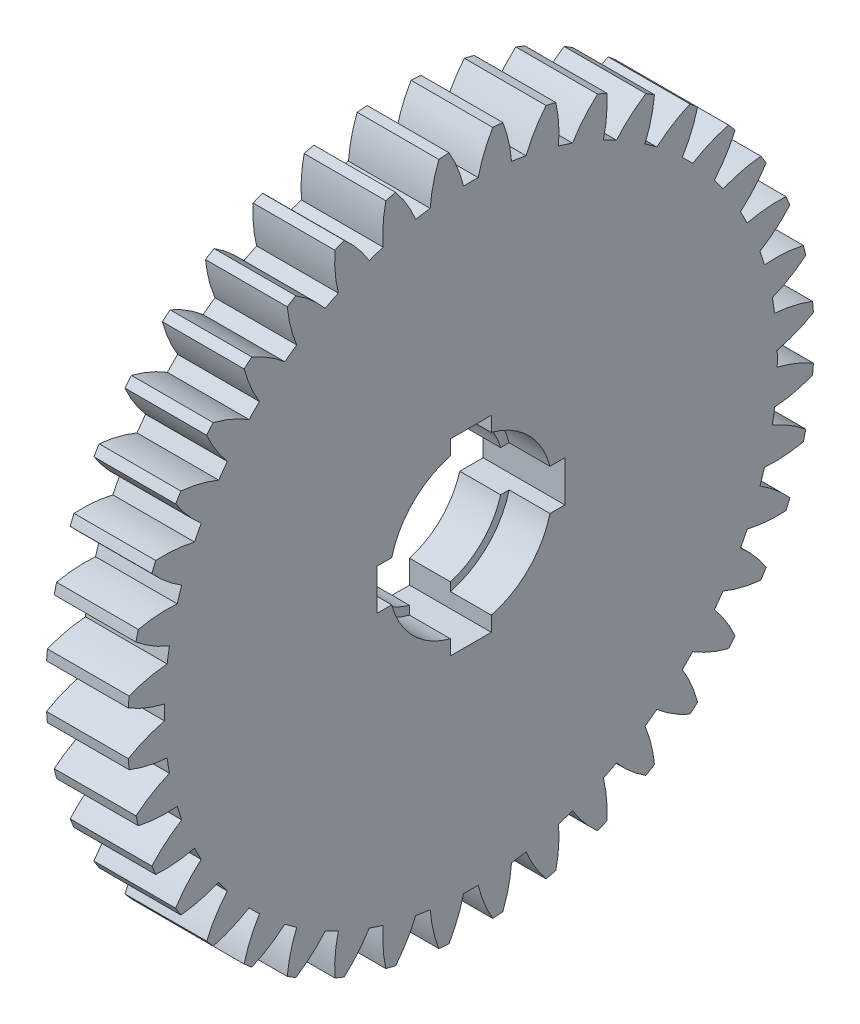
SolidWorks part; units mm, degrees
ref_plane "Plane1" through (0, 0, 0) normal (0, 0, 1) x (1, 0, 0)
ref_plane "Plane2" through (0, 0, 0) normal (0, 1, 0) x (1, 0, 0)
ref_plane "Plane3" through (0, 0, 0) normal (1, 0, 0) x (0, 0, -1)
sketch "HoldingSke" plane through (0, 0, 0) normal (0, 1, 0) x (1, 0, 0)
  line L0 (0, 0) -> (0.766, -0.6428)
  line L1 (-15, 0) -> (100, 0) construction
  line L2 (0, 0) -> (-2.1039, 2.3779)
  line L3 (0, 0) -> (-11.863, 4.5341)
  line L4 (0, 0) -> (6.6156, 5.5511)
  line L5 (0, 0) -> (-46.8476, -17.4728)
  line L6 (0, 0) -> (-6.6317, -4.4744)
  line L7 (-2.1039, 2.3779) -> (8.6586, 51.2059)
  line L8 (-76.2, 54.61) -> (-75.3, 54.61)
  line L9 (-71.009, 38.7566) -> (-53.1078, 45.2721)
  line L10 (-76.2, 71.12) -> (104.1128, 71.12)
  line L11 (0, 0) -> (-8, 0)
  line L12 (-76.2, 101.6) -> (-76.162, 101.6)
  line L13 (24.9733, 27.94) -> (52.9518, 28.4284)
  line L14 (24.9733, 27.94) -> (24.9743, 27.94)
  line L15 (24.9733, 27.94) -> (100.4006, 29.5858)
  line L16 (-63.627, -1) -> (-12.827, -1)
  circle A0 centre (0, 0) radius 2.5
  circle A1 centre (0, 0) radius 18.749
  circle A2 centre (0, 0) radius 37.5
  circle A3 centre (0, 0) radius 2.5
  dimension "MHD" = 37.498
  dimension "Hub_dia" = 75
  dimension "Bore" = 5
  dimension "MBD" = 5
  dimension "Num_teeth" = 40
  dimension "Pitch" = 1
  dimension "Overall_len" = 50
  dimension "Show_teeth" = 40
  dimension "Thickness" = 8
  dimension "OAL" = 50.0001
  dimension "T_dim" = 0.9
  dimension "Ap" = 20
  dimension "H" = 19.05
  dimension "Pitch_radius" = 180.3128
  dimension "Width" = 8
  dimension "Backlash" = 0.038
  dimension "Addendum_fac" = 1
  dimension "Dedendum_fac" = 1.25
  dimension "Clearance_fac" = 0.25
  dimension "Dedendum_add" = 0.001
  dimension "Module" = 1
sketch "BasProSke" plane through (0, 0, 0) normal (0, 1, 0) x (1, 0, 0)
  line L0 (-10, 0) -> (60, 0) construction
  line L1 (0, 0) -> (0, 21)
  line L2 (0, 0) -> (8, 0)
  line L3 (8, 0) -> (8, 21)
  line L4 (8, 21) -> (0, 21)
  dimension "Thickness" = 8
  dimension "Diameter" = 42
revolve "Base-Revolve" add sketch "BasProSke" angle 360 about L0
sketch "TooCutSke" plane through (0, 0, 0) normal (1, 0, 0) x (0, 0, -1)
  line L1 (0, 0) -> (0, 107) construction
  line L2 (0, 0) -> (-0.8517, 19.9819) construction
  line L3 (0, 0) -> (-3.1363, 39.8509) construction
  line L4 (-0.8517, 19.9819) -> (-1.5682, 19.9255) construction
  arc A0 (0.4487, 18.7436) -> (-0.4487, 18.7436) centre (0, 0) ccw
  arc A1 (1.3547, 20.9817) -> (-1.3547, 20.9817) centre (0, 0) ccw
  circle A2 centre (0, 0) radius 20 construction
  circle A3 centre (0, 0) radius 18.7939 construction
  arc A4 (-0.4487, 18.7436) -> (-1.3547, 20.9817) centre (-8.2322, 16.895) ccw
  arc A5 (1.3547, 20.9817) -> (0.4487, 18.7436) centre (8.2322, 16.895) ccw
  dimension "Root_dia" = 37.498
  dimension "Overcut_dia" = 42.0508
  dimension "Pitch_dia" = 40
  dimension "Base_dia" = 37.5877
  dimension "Flank_rad" = 8
  dimension "Half_ang" = 4.5
  dimension "Half_CT" = 0.7187
extrude "ToothCut" cut sketch "TooCutSke" along normal through all
fillet "Breaks" [suppressed] radius 0.02
fillet "RootFillets" [suppressed] radius 0.251
pattern_circular "TeethCuts" count 40 over 360 about axis through (0, 0, 0) along (1, 0, 0) of "ToothCut", "RootFillets", "Breaks"
sketch "HubNeaOneSke" plane through (0, 0, 0) normal (-1, 0, 0) x (0, 0, 1)
  circle A0 centre (0, 0) radius 18.749
  dimension "Diameter" = 37.498
extrude "HubNearOne" [suppressed] add sketch "HubNeaOneSke" along normal blind 42.0001
sketch "HubNeaBotSke" plane through (0, 0, 0) normal (-1, 0, 0) x (0, 0, 1)
  circle A0 centre (0, 0) radius 18.749
  dimension "Diameter" = 37.498
extrude "HubNearBoth" [suppressed] add sketch "HubNeaBotSke" along normal blind 21
ref_plane "FarPln" through (8, 0, 0) normal (1, 0, 0) x (0, 0, -1)
sketch "HubFarSke" plane through (8, 0, 0) normal (1, 0, 0) x (0, 0, -1)
  circle A0 centre (0, 0) radius 18.749
  dimension "Diameter" = 37.498
extrude "HubFar" [suppressed] add sketch "HubFarSke" along normal blind 21
sketch "BorSke" plane through (0, 0, 0) normal (1, 0, 0) x (0, 0, -1)
  circle A0 centre (0, 0) radius 2.5
  dimension "Diameter" = 5
extrude "Bore" cut sketch "BorSke" along normal mid plane 100.0001
sketch "KeySke" plane through (0, 0, 0) normal (1, 0, 0) x (0, 0, -1)
  line L0 (-1, 0) -> (-1, 3.4)
  line L1 (-1, 3.4) -> (1, 3.4)
  line L2 (1, 3.4) -> (1, 0)
  line L3 (0, 0) -> (0, 34) construction
  line L4 (-1, 0) -> (1, 0)
  dimension "Offset" = 3.4
  dimension "Width" = 2
extrude "Keyway" [suppressed] cut sketch "KeySke" along normal mid plane 100.0001
pattern_circular "Keyway2" [suppressed] count 2 every 90 about axis through (-10, 0, 0) along (1, 0, 0)
sketch "Sketch1" plane through (8, 0, 0) normal (1, 0, 0) x (0, 0, -1)
  circle A0 centre (-0.3641, 0) radius 30.3952
extrude "Cut-Extrude1" cut sketch "Sketch1" against normal blind 3
sketch "Sketch2" plane through (5, 0, 0) normal (1, 0, 0) x (0, 0, -1)
  line L3 (-1, -5.5) -> (1, -5.5) construction
  line L7 (5.5, 1) -> (4.0449, 1) construction
  line L8 (5.5, 1) -> (5.5, -1) construction
  line L9 (5.5, -1) -> (4.0449, -1) construction
  line L14 (5.3333, 0.8333) -> (3.9122, 0.8333) construction
  line L15 (5.3333, 0.8333) -> (5.3333, -0.8333) construction
  line L16 (5.3333, -0.8333) -> (3.9122, -0.8333) construction
  line L18 (-0.8333, -5.3333) -> (0.8333, -5.3333) construction
  line L20 (-3.9122, -0.8333) -> (-5.3333, -0.8333) construction
  line L21 (-5.3333, 0.8333) -> (-5.3333, -0.8333) construction
  line L22 (-3.9122, 0.8333) -> (-5.3333, 0.8333) construction
  line L36 (-1.25, 5.75) -> (1.25, 5.75)
  line L37 (1.25, 5.75) -> (1.25, 4.2361)
  line L38 (5.75, 1.25) -> (4.2361, 1.25)
  line L39 (5.75, 1.25) -> (5.75, -1.25)
  line L40 (5.75, -1.25) -> (4.2361, -1.25)
  line L41 (1.25, -4.2361) -> (1.25, -5.75)
  line L42 (-1.25, -5.75) -> (1.25, -5.75)
  line L43 (-1.25, -4.2361) -> (-1.25, -5.75)
  line L44 (-4.2361, -1.25) -> (-5.75, -1.25)
  line L45 (-5.75, 1.25) -> (-5.75, -1.25)
  line L46 (-4.2361, 1.25) -> (-5.75, 1.25)
  line L47 (-1.25, 5.75) -> (-1.25, 4.2361)
  line L51 (-1, -4.0449) -> (-1, -5.5) construction
  line L54 (1, -4.0449) -> (1, -5.5) construction
  line L59 (-1, 5.5) -> (-1, 4.0449) construction
  line L62 (-1, 5.5) -> (1, 5.5) construction
  line L65 (1, 5.5) -> (1, 4.0449) construction
  line L68 (-5.5, 1) -> (-5.5, -1) construction
  line L69 (-4.0449, 1) -> (-5.5, 1) construction
  line L71 (-4.0449, -1) -> (-5.5, -1) construction
  arc A7 (-0.8333, 3.9122) -> (-3.9122, 0.8333) centre (0, 0) ccw construction
  arc A12 (4.2361, 1.25) -> (1.25, 4.2361) centre (0, 0) ccw
  arc A13 (1.25, -4.2361) -> (4.2361, -1.25) centre (0, 0) ccw
  arc A14 (-4.2361, -1.25) -> (-1.25, -4.2361) centre (0, 0) ccw
  arc A15 (-1.25, 4.2361) -> (-4.2361, 1.25) centre (0, 0) ccw
  arc A17 (-4.0449, -1) -> (-1, -4.0449) centre (0, 0) ccw construction
  arc A19 (1, -4.0449) -> (4.0449, -1) centre (0, 0) ccw construction
  arc A23 (4.0449, 1) -> (1, 4.0449) centre (0, 0) ccw construction
  arc A25 (-1, 4.0449) -> (-4.0449, 1) centre (0, 0) ccw construction
  dimension "D1" = 0.25
extrude "Cut-Extrude2" cut sketch "Sketch2" against normal through all
sketch "Sketch3" plane through (5, 0, 0) normal (1, 0, 0) x (0, 0, -1)
  circle A0 centre (0, 0) radius 4.5
extrude "Cut-Extrude3" cut sketch "Sketch3" against normal blind 10
sketch "Sketch4" plane through (5, 0, 0) normal (1, 0, 0) x (0, 0, -1)
  circle A0 centre (0, 0) radius 5
extrude "Cut-Extrude4" cut sketch "Sketch4" against normal blind 2.5
equation "' \"Module@HoldingSke\" = 6.35"
equation "' \"Num_teeth@HoldingSke\" = 12"
equation "' \"Ap@HoldingSke\" =  20"
equation "' \"Ap@HoldingSke\" = 20"
equation "' \"Width@HoldingSke\" = 0.5 * 25.4"
equation "' \"Hub_dia@HoldingSke\"= 1 * 25.4"
equation "' \"Hub_dia@HoldingSke\" = 1 * 25.4"
equation "' \"Overall_len@HoldingSke\" = 1.0 * 25.4"
equation "' \"Bore@HoldingSke\" = 0.75 * 25.4"
equation "' \"T_dim@HoldingSke\" = 0.1 * 25.4"
equation "' \"Width@KeySke\" = 0.25 * 25.4"
equation "' \"Show_teeth@HoldingSke\" = 13"
equation "' \"Backlash@HoldingSke\" = 0.009 * 25.4"
equation "' \"Addendum_fac@HoldingSke\" = 1.0"
equation "' \"Dedendum_fac@HoldingSke\" = 1.25"
equation "' \"Dedendum_add@HoldingSke\" = 0.00005 * 25.4"
equation "' \"Clearance_fac@HoldingSke\" = 0.25"
equation "\"Pitch@HoldingSke\" = 1 / \"Module@HoldingSke\""
equation "\"Overcut_dia@TooCutSke\" = (\"Num_teeth@HoldingSke\" + 2 * \"Addendum_fac@HoldingSke\") / \"Pitch@HoldingSke\" + 0.002 * 25.4"
equation "\"Pitch_dia@TooCutSke\" = \"Num_teeth@HoldingSke\" / \"Pitch@HoldingSke\""
equation "\"Base_dia@TooCutSke\" = \"Num_teeth@HoldingSke\" / \"Pitch@HoldingSke\" * cos((\"Ap@HoldingSke\"  * 3.14159265 / 180))"
equation "\"Root_dia@TooCutSke\" = (\"Num_teeth@HoldingSke\" + 2) / \"Pitch@HoldingSke\" - 2 * (\"Addendum_fac@HoldingSke\" + \"Dedendum_fac@HoldingSke\") / \"Pitch@HoldingSke\" - \"Dedendum_add@HoldingSke\" * 2"
equation "\"Half_ang@TooCutSke\" = 180 / \"Num_teeth@HoldingSke\""
equation "\"Half_CT@TooCutSke\" = \"Num_teeth@HoldingSke\" / \"Pitch@HoldingSke\" * sin((3.14159265 / 2 / \"Num_teeth@HoldingSke\")) / 2 - 7 * \"Backlash@HoldingSke\" / 4"
equation "\"Flank_rad@TooCutSke\" = \"Num_teeth@HoldingSke\" / \"Pitch@HoldingSke\" / 5"
equation "\"Radius@RootFillets\" = \"Clearance_fac@HoldingSke\" / \"Pitch@HoldingSke\" + \"Dedendum_add@HoldingSke\""
equation "\"Break_rad@Breaks\" = 0.02 / \"Pitch@HoldingSke\""
equation "\"Thickness@HoldingSke\" = \"Width@HoldingSke\""
equation "\"OAL@HoldingSke\" = \"Thickness@HoldingSke\""
equation "\"MHD@HoldingSke\" = (\"Num_teeth@HoldingSke\" + 2) / \"Pitch@HoldingSke\" - 2 * (\"Addendum_fac@HoldingSke\" + \"Dedendum_fac@HoldingSke\")  / \"Pitch@HoldingSke\" - \"Dedendum_add@HoldingSke\" * 2"
equation "\"MBD@HoldingSke\" = (\"Num_teeth@HoldingSke\" + 2) / \"Pitch@HoldingSke\" - 2 * (\"Addendum_fac@HoldingSke\" + \"Dedendum_fac@HoldingSke\")  / \"Pitch@HoldingSke\" - \"Dedendum_add@HoldingSke\" * 2 - 0.002 * 25.4"
equation "\"MHD@HoldingSke\" = ((sgn( \"MHD@HoldingSke\" - \"Hub_dia@HoldingSke\" )-1)*( \"MHD@HoldingSke\" - \"Hub_dia@HoldingSke\" ))/-2+ \"Hub_dia@HoldingSke\""
equation "\"MBD@HoldingSke\" = ((sgn( \"MBD@HoldingSke\" - \"Bore@HoldingSke\" )-1)*( \"MBD@HoldingSke\" - \"Bore@HoldingSke\" ))/-2+ \"Bore@HoldingSke\""
equation "\"OAL@HoldingSke\" = ((sgn( \"OAL@HoldingSke\" - \"Overall_len@HoldingSke\" )+1)*( \"OAL@HoldingSke\" - \"Overall_len@HoldingSke\" ))/2 + \"Overall_len@HoldingSke\" + 0.000002 * 25.4"
equation "\"Num_teeth@TeethCuts\" = int( \"Show_teeth@HoldingSke\" ) + 1"
equation "\"Num_teeth@TeethCuts\" = ((sgn( \"Num_teeth@TeethCuts\" - \"Num_teeth@HoldingSke\" )-1)*( \"Num_teeth@TeethCuts\" - \"Num_teeth@HoldingSke\" ))/-2+ \"Num_teeth@HoldingSke\""
equation "\"Num_teeth@TeethCuts\" = ((sgn( \"Num_teeth@TeethCuts\" - 2.0)+1)*( \"Num_teeth@TeethCuts\" - 2.0))/2 +2.0"
equation "\"Angle@TeethCuts\" = 360.0 / \"Num_teeth@HoldingSke\""
equation "\"Diameter@BasProSke\" = (\"Num_teeth@HoldingSke\" + 2 * \"Addendum_fac@HoldingSke\") / \"Pitch@HoldingSke\""
equation "\"Thickness@BasProSke\"  = \"Thickness@HoldingSke\""
equation "' \"Fillet_rad@BasProSke\" =  \"Thickness@HoldingSke\" * 0.05"
equation "' \"Fillet_rad@BasProSke\" = \"Thickness@HoldingSke\" * 0.05"
equation "\"MHD@HoldingSke\" = ((sgn( \"MHD@HoldingSke\" - \"Root_dia@TooCutSke\" )-1)*( \"MHD@HoldingSke\" - \"Root_dia@TooCutSke\" ))/-2+ \"Root_dia@TooCutSke\""
equation "\"Diameter@HubNeaOneSke\" = \"MHD@HoldingSke\""
equation "\"Length@HubNearOne\" = \"OAL@HoldingSke\" - \"Thickness@BasProSke\""
equation "\"Diameter@HubNeaBotSke\" = \"MHD@HoldingSke\""
equation "\"Length@HubNearBoth\" = ( \"OAL@HoldingSke\" - \"Thickness@BasProSke\" ) / 2.0"
equation "\"Thickness@FarPln\" = \"Thickness@BasProSke\""
equation "\"Diameter@HubFarSke\" = \"MHD@HoldingSke\""
equation "\"Length@HubFar\" = ( \"OAL@HoldingSke\" - \"Thickness@BasProSke\" ) / 2.0"
equation "\"Diameter@BorSke\" = \"MBD@HoldingSke\""
equation "\"D1@Bore\" = \"OAL@HoldingSke\" * 2.0"
equation "\"D1@Keyway\" = \"OAL@HoldingSke\" * 2.0"
equation "\"Offset@KeySke\" = \"T_dim@HoldingSke\" + \"MBD@HoldingSke\" / 2.0"
